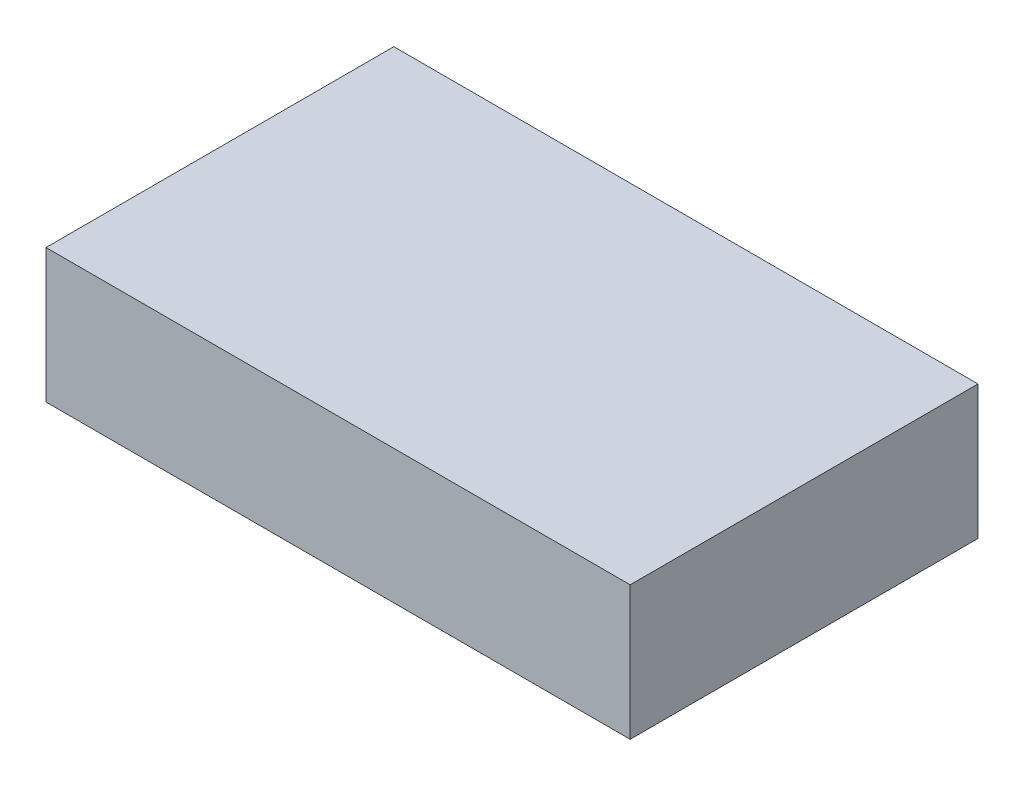
SolidWorks part; units mm, degrees
ref_plane "Front Plane" through (0, 0, 0) normal (0, 0, 1) x (1, 0, 0)
ref_plane "Top Plane" through (0, 0, 0) normal (0, 1, 0) x (1, 0, 0)
ref_plane "Right Plane" through (0, 0, 0) normal (1, 0, 0) x (0, 0, -1)
sketch "Sketch1" plane through (0, 0, 0) normal (0, 1, 0) x (1, 0, 0)
  line L1 (-55, 32.75) -> (55, 32.75)
  line L2 (-55, 32.75) -> (-55, -32.75)
  line L3 (-55, -32.75) -> (55, -32.75)
  line L4 (55, 32.75) -> (55, -32.75)
  line L5 (-55, 32.75) -> (55, -32.75) construction
  line L6 (-55, -32.75) -> (55, 32.75) construction
  point P0 (0, 0)
  dimension "D1" = 110
  dimension "D2" = 65.5
extrude "Boss-Extrude1" add sketch "Sketch1" along normal blind 25.2
